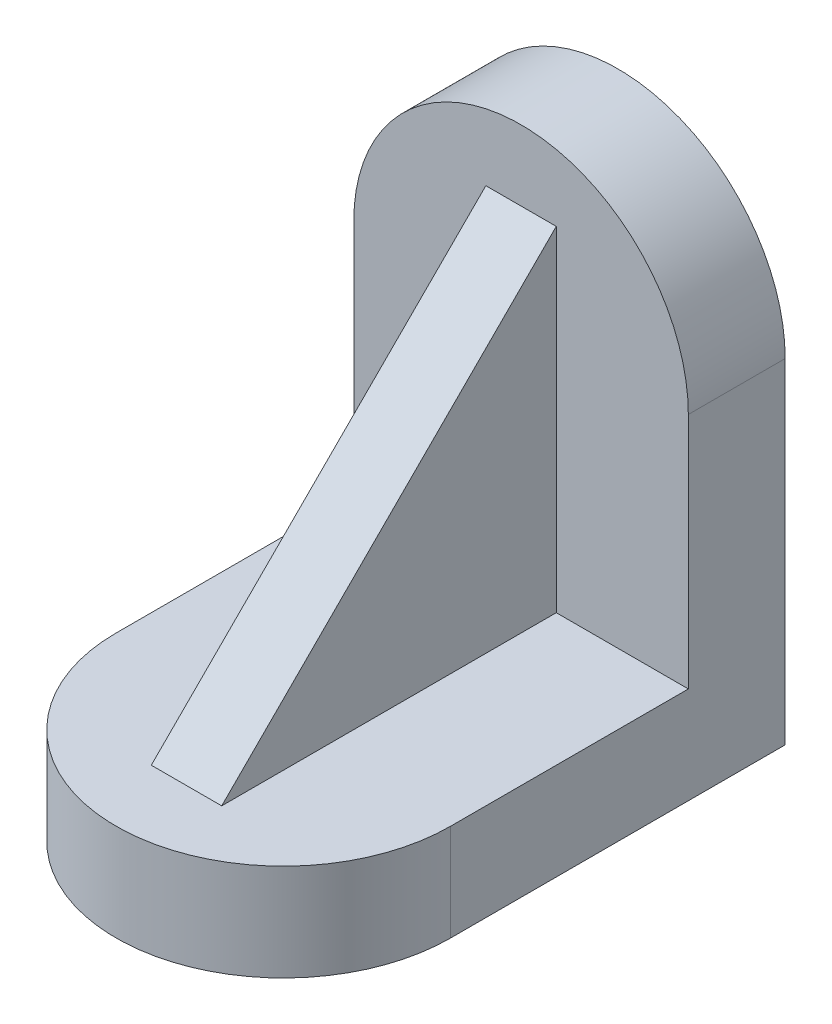
SolidWorks part; units mm, degrees
ref_plane "Front Plane" through (0, 0, 0) normal (0, 0, 1) x (1, 0, 0)
ref_plane "Top Plane" through (0, 0, 0) normal (0, 1, 0) x (1, 0, 0)
ref_plane "Right Plane" through (0, 0, 0) normal (1, 0, 0) x (0, 0, -1)
sketch "Sketch2" plane through (0, 0, 0) normal (0, 1, 0) x (1, 0, 0)
  line L2 (0, 0) -> (0, 38)
  line L3 (0, 38) -> (38, 38)
  line L4 (38, 0) -> (38, 38)
  arc A0 (0, 0) -> (38, 0) centre (19, 0) ccw
  point P6 (19, -19)
  dimension "D3" = 57
  dimension "D1" = 38
  dimension "D2" = 38
extrude "Boss-Extrude1" add sketch "Sketch2" along normal blind 11
sketch "Sketch3" plane through (0, 0, -38) normal (0, 0, -1) x (-1, 0, 0)
  line L1 (-38, 0) -> (0, 0)
  line L2 (-38, 0) -> (-38, 38)
  line L4 (0, 0) -> (0, 38)
  arc A0 (0, 38) -> (-38, 38) centre (-19, 38) ccw
  dimension "D1" = 38
  dimension "D2" = 38
extrude "Boss-Extrude4" add sketch "Sketch3" against normal blind 11
ref_plane "Plane3" through (19, 0, 0) normal (-1, 0, 0) x (0, 0, 1)
sketch "Sketch9" plane through (19, 0, 0) normal (-1, 0, 0) x (0, 0, 1)
  line L0 (-27, 49) -> (11, 11)
  point P0 (-27, 49)
  point P7 (11, 11)
rib "Rib1" sketch "Sketch9" sketch "Sketch9" thickness 8 extrusion direction parallel to sketch draft on no parameters "D1"=8
